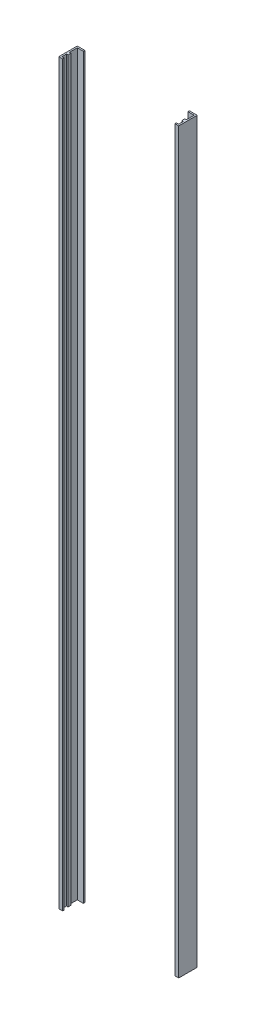
SolidWorks part; units mm, degrees
ref_plane "Front Plane" through (0, 0, 0) normal (0, 0, 1) x (1, 0, 0)
ref_plane "Top Plane" through (0, 0, 0) normal (0, 1, 0) x (1, 0, 0)
ref_plane "Right Plane" through (0, 0, 0) normal (1, 0, 0) x (0, 0, -1)
sketch "Sketch1" plane through (0, 0, 0) normal (0, 1, 0) x (1, 0, 0)
  line L0 (-86.36, 0) -> (86.36, 0) construction
  line L1 (-86.36, 0) -> (-99.06, 0) construction
  line L2 (86.36, 0) -> (99.06, 0) construction
  line L3 (-92.71, 0) -> (-99.06, 0)
  line L4 (-99.06, 0) -> (-99.06, 30.48)
  line L5 (-99.06, 30.48) -> (-92.71, 30.48)
  line L11 (-92.71, 2.54) -> (-96.52, 2.54)
  line L12 (-96.52, 2.54) -> (-96.52, 10.16)
  line L13 (-96.52, 27.94) -> (-92.71, 27.94)
  line L15 (-92.71, 2.54) -> (-92.71, 0)
  line L16 (-96.52, 10.16) -> (-93.98, 10.16)
  line L17 (-93.98, 10.16) -> (-93.98, 15.24)
  line L18 (-93.98, 15.24) -> (-96.52, 15.24)
  line L19 (-96.52, 15.24) -> (-96.52, 27.94)
  line L20 (0, 0) -> (0, 40.7394) construction
  line L21 (-96.52, 2.54) -> (-96.52, 27.94) construction
  line L22 (92.71, 2.54) -> (92.71, 0)
  line L23 (92.71, 0) -> (99.06, 0)
  line L24 (99.06, 0) -> (99.06, 30.48)
  line L25 (96.52, 15.24) -> (96.52, 27.94)
  line L26 (93.98, 15.24) -> (96.52, 15.24)
  line L27 (93.98, 10.16) -> (93.98, 15.24)
  line L28 (96.52, 10.16) -> (93.98, 10.16)
  line L30 (96.52, 27.94) -> (92.71, 27.94)
  line L31 (96.52, 2.54) -> (96.52, 10.16)
  line L32 (92.71, 2.54) -> (96.52, 2.54)
  line L33 (99.06, 30.48) -> (92.71, 30.48)
  line L34 (-92.71, 30.48) -> (-86.36, 30.48)
  line L35 (-86.36, 27.94) -> (-92.71, 27.94)
  line L36 (-86.36, 30.48) -> (-86.36, 27.94)
  line L37 (86.36, 27.94) -> (92.71, 27.94)
  line L38 (86.36, 30.48) -> (86.36, 27.94)
  line L39 (92.71, 30.48) -> (86.36, 30.48)
  point P3 (0, 0)
  dimension "D1" = 172.72
  dimension "D2" = 12.7
  dimension "D3" = 30.48
  dimension "D5" = 7.62
  dimension "D6" = 5.08
  dimension "D7" = 2.54
  dimension "D8" = 12.7
  dimension "D4" = 2.54
extrude "Boss-Extrude1" add sketch "Sketch1" along normal blind 1219.2
